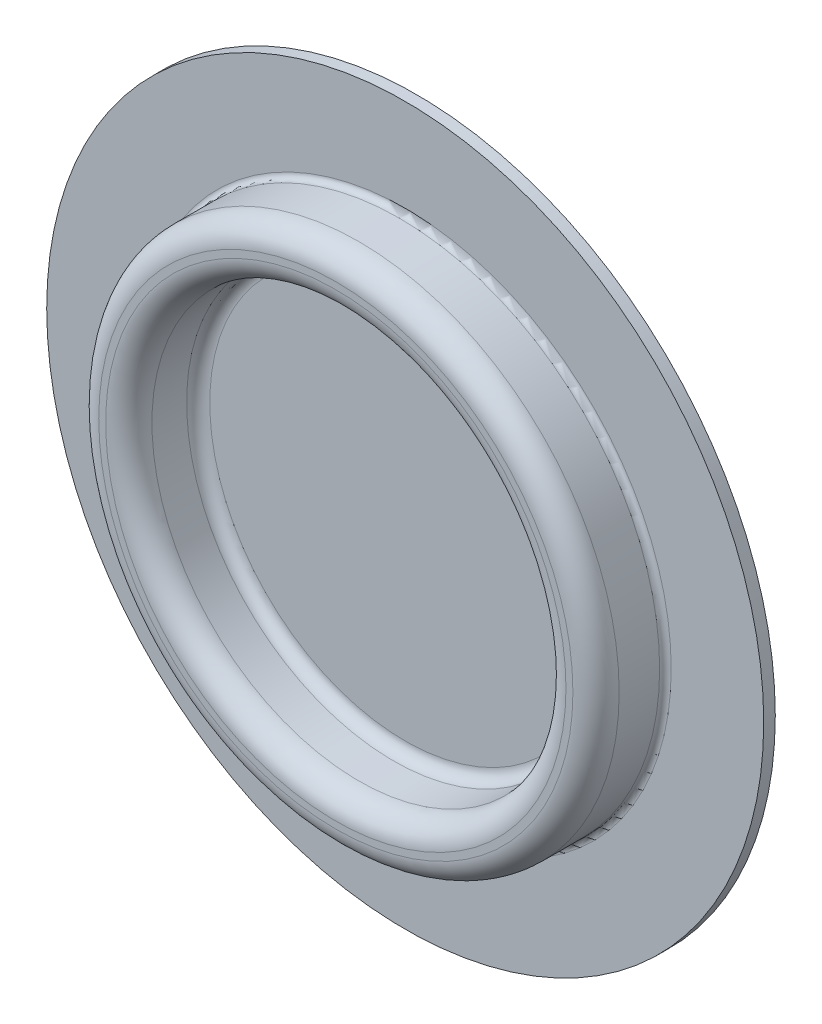
SolidWorks part; units mm, degrees
material "AISI 1020"
ref_plane "Alzado" through (0, 0, 0) normal (0, 0, 1) x (1, 0, 0)
ref_plane "Planta" through (0, 0, 0) normal (0, 1, 0) x (1, 0, 0)
ref_plane "Vista lateral" through (0, 0, 0) normal (1, 0, 0) x (0, 0, -1)
sketch "Croquis1" plane through (0, 0, 0) normal (1, 0, 0) x (0, 0, -1)
  line L0 (-74.477, 0) -> (11.1711, 0) construction
  line L1 (-1, 31) -> (-1, 23)
  line L2 (-1.5, 22.5) -> (-5, 22.5)
  line L3 (-7, 20.5) -> (-7, 19.9)
  line L4 (-5, 17.9) -> (-2, 17.9)
  line L11 (0, 31) -> (0, 23)
  line L12 (-1.5, 21.5) -> (-5, 21.5)
  line L13 (-6, 20.5) -> (-6, 19.9)
  line L14 (-5, 18.9) -> (-2, 18.9)
  line L15 (-1, 31) -> (0, 31)
  line L16 (0, 0) -> (-1, 0)
  line L17 (0, 21.5) -> (-5, 21.5) construction
  line L18 (0, 31) -> (0, 21.5) construction
  line L19 (-1, 0) -> (-1, 16.9)
  line L21 (0, 0) -> (0, 16.9)
  line L22 (-5, 17.9) -> (-1.2754, 17.9) construction
  line L23 (-5, 18.9) -> (1.5978, 18.9) construction
  line L24 (-1, -27) -> (-1, 27) construction
  line L25 (-1, 31) -> (-1, 22.5) construction
  line L26 (-1, 22.5) -> (-5, 22.5) construction
  arc A1 (-7, 19.9) -> (-5, 17.9) centre (-5, 19.9) ccw
  arc A2 (-5, 22.5) -> (-7, 20.5) centre (-5, 20.5) ccw
  arc A9 (-5, 21.5) -> (-6, 20.5) centre (-5, 20.5) ccw
  arc A10 (-6, 19.9) -> (-5, 18.9) centre (-5, 19.9) ccw
  arc A13 (-1.5, 21.5) -> (0, 23) centre (-1.5, 23) ccw
  arc A14 (-0.0214, 23.5922) -> (0, 0) centre (-13025.2886, 0) cw construction
  arc A15 (-1.0201, 22.8967) -> (-1, 0) centre (-13025.2886, 0) cw construction
  arc A16 (1.5978, 18.9) -> (-0.0214, 23.5922) centre (-1.6013, 20.4215) cw construction
  arc A17 (-1.2754, 17.9) -> (-1.0201, 22.8967) centre (-1.6013, 20.4215) cw construction
  arc A18 (-2, 17.9) -> (-1, 16.9) centre (-2, 16.9) cw
  arc A19 (-2, 18.9) -> (0, 16.9) centre (-2, 16.9) cw
  arc A20 (-1, 23) -> (-1.5, 22.5) centre (-1.5, 23) cw
  dimension "D1" = 1
  dimension "D2" = 1
  dimension "D4" = 2
  dimension "D5" = 2
  dimension "D6" = 1.5
  dimension "D9" = 0.5
  dimension "D3" = 6
  dimension "D7" = 45
  dimension "D8" = 62
  dimension "D10" = 2.6
revolve "Revolución1" add sketch "Croquis1" angle 360 about L0
